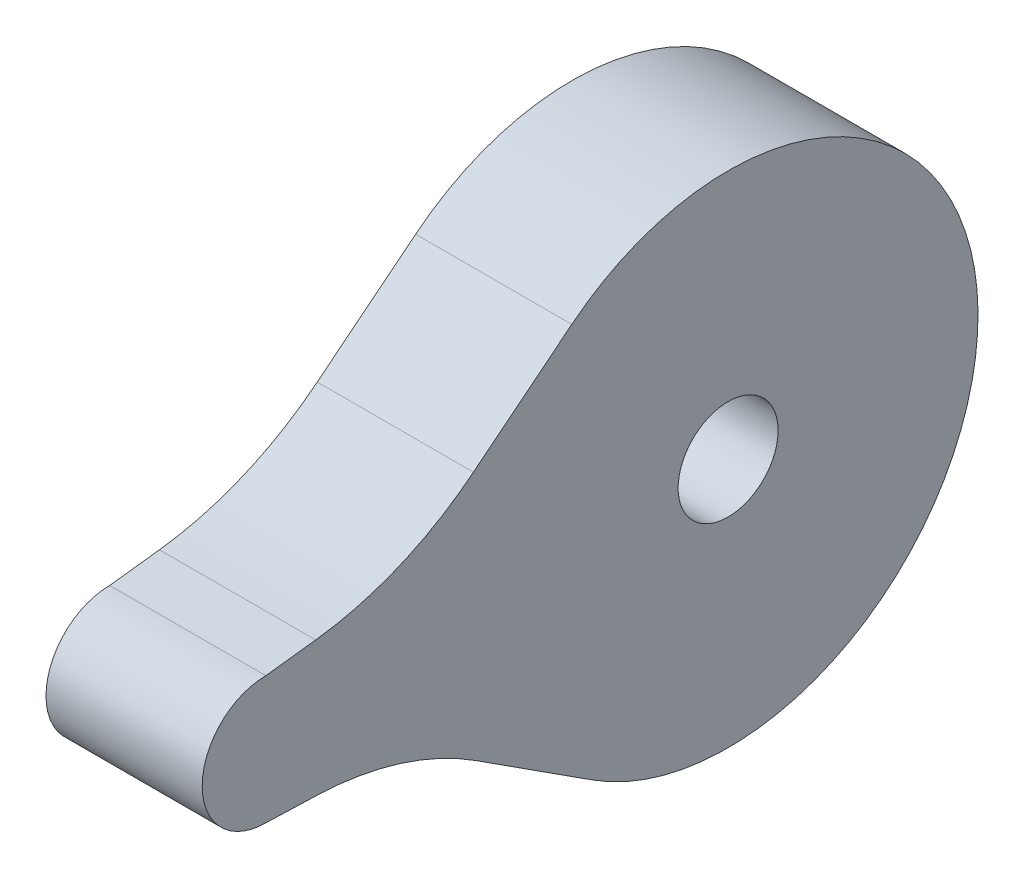
SolidWorks part; units mm, degrees
ref_plane "Front Plane" through (0, 0, 0) normal (0, 0, 1) x (1, 0, 0)
ref_plane "Top Plane" through (0, 0, 0) normal (0, 1, 0) x (1, 0, 0)
ref_plane "Right Plane" through (0, 0, 0) normal (1, 0, 0) x (0, 0, -1)
sketch "Sketch2" plane through (0, 0, 0) normal (1, 0, 0) x (0, 0, -1)
  circle A0 centre (0, 0) radius 1.6
  circle A1 centre (0, 0) radius 8
extrude "Boss-Extrude1" add sketch "Sketch2" along normal blind 5 contours A1 | A0
sketch "Sketch3" plane through (5, 0, 0) normal (1, 0, 0) x (0, 0, -1)
  line L0 (0, 0) -> (-10.3753, -0.449)
  line L1 (-10.3753, -0.449) -> (-14.7962, -0.6403)
  line L2 (-14.7962, 1.3997) -> (-10.3753, 1.936)
  line L3 (-14.7962, -2.6803) -> (-10.3753, -2.834)
  line L4 (-10.3753, -2.834) -> (-4.3313, -6.7261)
  line L5 (-10.3753, 1.936) -> (-5.0037, 6.242)
  circle A0 centre (-10.3753, -0.449) radius 2.385
  circle A1 centre (0, 0) radius 8 construction
  circle A2 centre (-14.7962, -0.6403) radius 2.04
  circle A3 centre (0, 0) radius 8
  arc A4 (-14.7962, 1.3997) -> (-13.3715, 0.8198) centre (-14.7962, -0.6403) ccw
  point P14 (-2.5052, 7.5976)
  point P16 (-10.743, 1.9075)
extrude "Boss-Extrude2" add sketch "Sketch3" against normal blind 5
fillet "Fillet1" radius 10 1 edges at (2.5, 1.936, 10.3753)
fillet "Fillet2" radius 10 1 edges at (2.5, -2.834, 10.3753)
